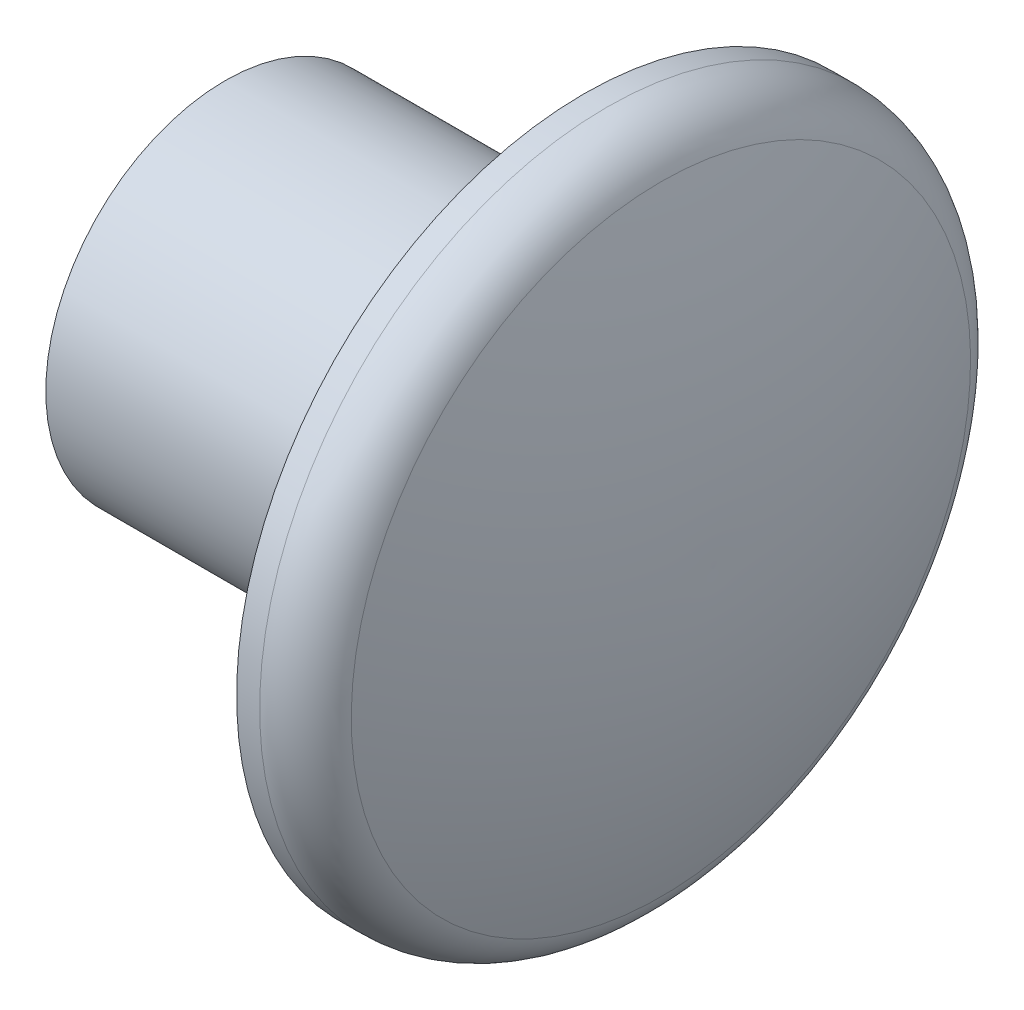
SolidWorks part; units mm, degrees
ref_plane "Front Plane" through (0, 0, 0) normal (0, 0, 1) x (1, 0, 0)
ref_plane "Top Plane" through (0, 0, 0) normal (0, 1, 0) x (1, 0, 0)
ref_plane "Right Plane" through (0, 0, 0) normal (1, 0, 0) x (0, 0, -1)
sketch "Sketch10" plane through (34.2682, 0, 0) normal (0, 0, 1) x (1, 0, 0)
  line L0 (11.0723, -46.7198) -> (19.0098, -46.7198)
  line L2 (19.0098, -46.7198) -> (19.0098, -50.4358)
  line L5 (11.0723, -46.7198) -> (11.0723, -42.751)
  line L6 (21.8673, -42.751) -> (11.0723, -42.751)
  line L8 (19.0098, -50.4358) -> (19.5197, -50.4358)
  arc A0 (21.8673, -42.751) -> (20.7125, -49.6017) centre (2.8199, -43.0629) cw
  arc A1 (19.5197, -50.4358) -> (20.7125, -49.6017) centre (19.5197, -49.1658) ccw
  point P13 (20.3853, -50.4358)
  dimension "D5" = 19.05
  dimension "D6" = 1.27
  dimension "D1" = 7.9375
  dimension "D3" = 3.9624
  dimension "D4" = 3.9688
revolve "Revolve1" add sketch "Sketch10" angle 360 about L6
